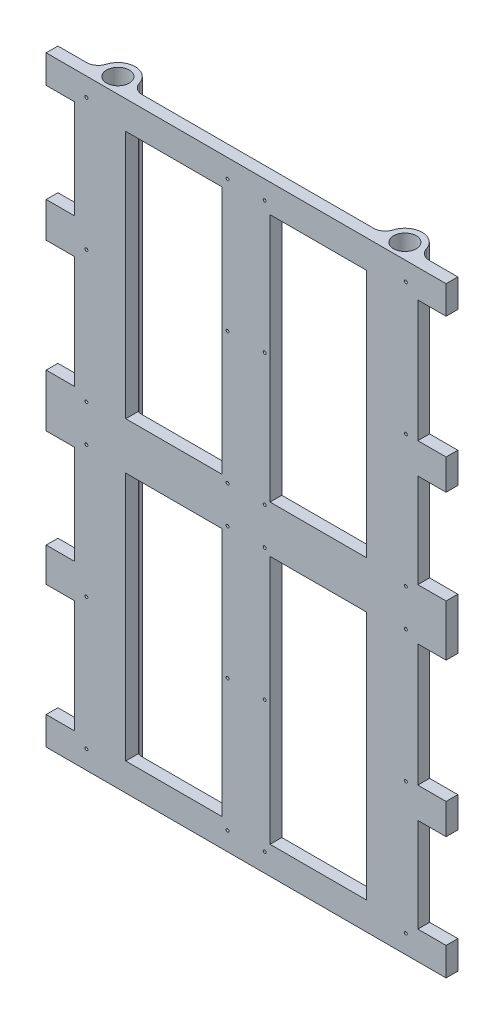
SolidWorks part; units mm, degrees
material "E-Glass Fiber"
ref_plane "Front Plane" through (0, 0, 0) normal (0, 0, 1) x (1, 0, 0)
ref_plane "Top Plane" through (0, 0, 0) normal (0, 1, 0) x (1, 0, 0)
ref_plane "Right Plane" through (0, 0, 0) normal (1, 0, 0) x (0, 0, -1)
other "Center of Mass"
sketch "Sketch1" plane through (0, 0, 0) normal (0, 1, 0) x (1, 0, 0)
  line L19 (85, -5) -> (85, 0)
  line L20 (85, -5) -> (-85, -5)
  line L24 (85, 0) -> (72.8176, 0)
  line L25 (-85, -5) -> (-85, 0)
  line L26 (85, -5) -> (-85, 0) construction
  line L27 (85, 0) -> (-85, -5) construction
  line L28 (0, 0) -> (0, -5) construction
  line L29 (-72.8176, 0) -> (-85, 0)
  line L30 (49.1824, 0) -> (-49.1824, 0)
  circle A29 centre (-61, 1.5) radius 4.825
  arc A30 (-68.1698, 0) -> (-53.8302, 0) centre (-61, 1.5) ccw construction
  arc A31 (-72.8176, 0) -> (-68.0234, 3.5801) centre (-72.8176, 5) ccw
  arc A32 (-53.9766, 3.5801) -> (-49.1824, 0) centre (-49.1824, 5) ccw
  arc A33 (-53.9766, 3.5801) -> (-68.0234, 3.5801) centre (-61, 1.5) ccw
  arc A34 (68.1698, 0) -> (53.8302, 0) centre (61, 1.5) cw construction
  arc A35 (53.9766, 3.5801) -> (68.0234, 3.5801) centre (61, 1.5) cw
  arc A36 (53.9766, 3.5801) -> (49.1824, 0) centre (49.1824, 5) cw
  arc A37 (72.8176, 0) -> (68.0234, 3.5801) centre (72.8176, 5) cw
  circle A38 centre (61, 1.5) radius 4.825
  point P1 (0, -2.5)
  dimension "D3" = 9.65
  dimension "D4" = 6.5
  dimension "D5" = 61
  dimension "D6" = 14.65
  dimension "D1" = 5
  dimension "D2" = 170
extrude "Boss-Extrude1" add sketch "Sketch1" along normal blind 255.6
sketch "Sketch2" plane through (0, 0, 0) normal (0, 0, -1) x (-1, 0, 0)
  line L0 (-85, 127.8) -> (85, 127.8) construction
  line L1 (-51.175, 11.8) -> (-10.175, 11.8)
  line L2 (-51.175, 11.8) -> (-51.175, 117.8)
  line L3 (-51.175, 243.6) -> (-10.175, 243.6)
  line L4 (-10.175, 11.8) -> (-10.175, 117.8)
  line L5 (-51.175, 11.8) -> (-10.175, 243.6) construction
  line L6 (-51.175, 243.6) -> (-10.175, 11.8) construction
  line L7 (-49.1824, 255.6) -> (49.1824, 255.6) construction
  line L8 (-10.175, 137.8) -> (-10.175, 243.6)
  line L9 (0, 255.6) -> (0, 0) construction
  line L10 (-93, 178.8) -> (-73, 178.8)
  line L11 (51.175, 11.8) -> (10.175, 11.8)
  line L12 (51.175, 11.8) -> (51.175, 117.8)
  line L13 (51.175, 243.6) -> (10.175, 243.6)
  line L14 (10.175, 11.8) -> (10.175, 117.8)
  line L15 (51.175, 11.8) -> (10.175, 243.6) construction
  line L16 (51.175, 243.6) -> (10.175, 11.8) construction
  line L17 (-56.175, 0) -> (-56.175, 255.6) construction
  line L18 (56.175, 255.6) -> (56.175, 0) construction
  line L19 (10.175, 137.8) -> (10.175, 243.6)
  line L20 (-51.175, 117.8) -> (-10.175, 117.8)
  line L22 (-51.175, 137.8) -> (-10.175, 137.8)
  line L24 (10.175, 137.8) -> (51.175, 137.8)
  line L25 (10.175, 117.8) -> (51.175, 117.8)
  line L26 (-51.175, 137.8) -> (-51.175, 243.6)
  line L27 (51.175, 137.8) -> (51.175, 243.6)
  line L28 (-93, 178.8) -> (-93, 138.8)
  line L29 (-93, 138.8) -> (-73, 138.8)
  line L30 (-73, 178.8) -> (-73, 138.8)
  line L31 (-93, 178.8) -> (-73, 138.8) construction
  line L32 (-93, 138.8) -> (-73, 178.8) construction
  line L33 (-85, 255.6) -> (-85, 0) construction
  line L34 (85, 255.6) -> (85, 0) construction
  line L35 (-93, 52) -> (-73, 52)
  line L36 (-73, 191.8) -> (-93, 191.8)
  line L37 (-73, 191.8) -> (-73, 243.6)
  line L38 (-73, 243.6) -> (-93, 243.6)
  line L39 (-93, 191.8) -> (-93, 243.6)
  line L40 (-73, 191.8) -> (-93, 243.6) construction
  line L41 (-73, 243.6) -> (-93, 191.8) construction
  line L42 (-93, 52) -> (-93, 12)
  line L43 (-93, 12) -> (-73, 12)
  line L44 (-73, 52) -> (-73, 12)
  line L53 (-93, 52) -> (-73, 12) construction
  line L54 (-93, 12) -> (-73, 52) construction
  line L55 (-73, 65) -> (-93, 65)
  line L56 (-73, 65) -> (-73, 117)
  line L57 (-73, 117) -> (-93, 117)
  line L58 (-93, 65) -> (-93, 117)
  line L59 (-73, 65) -> (-93, 117) construction
  line L60 (-73, 117) -> (-93, 65) construction
  line L61 (72.8176, 255.6) -> (85, 255.6) construction
  line L62 (-85, 0) -> (-72.8176, 0) construction
  line L67 (93, 201.6) -> (73, 201.6)
  line L68 (93, 201.6) -> (93, 243.6)
  line L73 (93, 243.6) -> (73, 243.6)
  line L74 (73, 201.6) -> (73, 243.6)
  line L75 (-85, 255.6) -> (-72.8176, 255.6) construction
  line L76 (93, 74.4) -> (73, 74.4)
  line L77 (93, 201.6) -> (73, 243.6) construction
  line L78 (93, 243.6) -> (73, 201.6) construction
  line L83 (73, 138.8) -> (93, 138.8)
  line L84 (73, 138.8) -> (73, 186.6)
  line L85 (73, 186.6) -> (93, 186.6)
  line L86 (93, 138.8) -> (93, 186.6)
  line L87 (73, 138.8) -> (93, 186.6) construction
  line L88 (73, 186.6) -> (93, 138.8) construction
  line L89 (93, 74.4) -> (93, 116.4)
  line L90 (93, 116.4) -> (73, 116.4)
  line L91 (73, 74.4) -> (73, 116.4)
  line L92 (93, 74.4) -> (73, 116.4) construction
  line L93 (93, 116.4) -> (73, 74.4) construction
  line L94 (73, 12) -> (93, 12)
  line L95 (73, 12) -> (73, 59.9)
  line L96 (73, 59.9) -> (93, 59.9)
  line L97 (93, 12) -> (93, 59.9)
  line L98 (73, 12) -> (93, 59.9) construction
  line L99 (73, 59.9) -> (93, 12) construction
  line L100 (72.8176, 0) -> (85, 0) construction
  point P0 (-30.675, 127.7)
  point P5 (-83, 158.8)
  point P14 (30.675, 127.7)
  point P23 (0, 127.8)
  point P39 (-83, 217.7)
  point P44 (-83, 32)
  point P49 (-83, 91)
  point P54 (83, 222.6)
  point P61 (83, 162.7)
  point P70 (83, 95.4)
  point P75 (83, 35.95)
  dimension "D1" = 12
  dimension "D2" = 5
  dimension "D3" = 41
  dimension "D4" = 12
  dimension "D5" = 5
  dimension "D6" = 41
  dimension "D7" = 20
  dimension "D8" = 11
  dimension "D9" = 40
  dimension "D10" = 73
  dimension "D11" = 20
  dimension "D12" = 13
  dimension "D13" = 12
  dimension "D14" = 40
  dimension "D15" = 20
  dimension "D16" = 13
  dimension "D17" = 52
  dimension "D18" = 73
  dimension "D19" = 20
  dimension "D20" = 12
  dimension "D21" = 12
  dimension "D22" = 15
  dimension "D23" = 42
  dimension "D24" = 73
  dimension "D25" = 11
  dimension "D26" = 20
  dimension "D27" = 14.5
  dimension "D28" = 42
  dimension "D29" = 73
  dimension "D30" = 12
extrude "Cut-Extrude2" cut sketch "Sketch2" against normal through all and the other way through all
sketch "Sketch3" plane through (0, 0, 5) normal (0, 0, -1) x (-1, 0, 0)
  line L0 (0, 0) -> (0, 255.6) construction
  line L1 (-49.1824, 0) -> (49.1824, 0) construction
  line L5 (255.8, 127.8) -> (0, 127.8) construction
  point P0 (-67.9, 7.9)
  point P1 (-7.9, 7.9)
  point P3 (-7.9, 63.9)
  point P5 (-67.9, 63.9)
  point P7 (-67.9, 119.9)
  point P9 (-7.9, 119.9)
  point P23 (7.9, 119.9)
  point P24 (67.9, 119.9)
  point P25 (67.9, 63.9)
  point P26 (7.9, 63.9)
  point P27 (7.9, 7.9)
  point P28 (67.9, 7.9)
  point P31 (67.9, 247.7)
  point P32 (7.9, 247.7)
  point P33 (7.9, 191.7)
  point P34 (67.9, 191.7)
  point P35 (67.9, 135.7)
  point P36 (7.9, 135.7)
  point P37 (-7.9, 135.7)
  point P38 (-67.9, 135.7)
  point P39 (-67.9, 191.7)
  point P40 (-7.9, 191.7)
  point P41 (-7.9, 247.7)
  point P42 (-67.9, 247.7)
hole_wizard "Ø1.25 (1.25) Diameter Hole1" positions "Sketch3" profile "Sketch4" hole size "Ø1.25" standard "ANSI Metric" end condition through all
sketch "Sketch4" plane through (67.9, 7.9, 5) normal (1, 0, 0) x (0, -1, 0)
  line L0 (0, 0) -> (0, 13.825)
  line L1 (0, 13.825) -> (0.625, 13.825)
  line L2 (0.625, 13.825) -> (0.625, 0)
  line L5 (0.625, 0) -> (0, 0)
  line L11 (0, -6.35) -> (0, 107.95) construction
  dimension "Thru Hole Dia." = 1.25
  dimension "Thru Hole Depth" = 13.825
sketch "Sketch5" plane through (0, 0, 0) normal (0, 0, -1) x (-1, 0, 0)
  line L0 (255.8, 127.8) -> (0, 127.8) construction
  line L1 (0, 255.6) -> (0, 127.8) construction
  circle A24 centre (-67.9, 247.7) radius 1.5
  circle A25 centre (-7.9, 247.7) radius 1.5
  circle A26 centre (-67.9, 191.7) radius 1.5
  circle A27 centre (-67.9, 135.7) radius 1.5
  circle A28 centre (-7.9, 135.7) radius 1.5
  circle A29 centre (-7.9, 191.7) radius 1.5
  circle A30 centre (-7.9, 63.9) radius 1.5
  circle A31 centre (-7.9, 119.9) radius 1.5
  circle A32 centre (-67.9, 119.9) radius 1.5
  circle A33 centre (-67.9, 63.9) radius 1.5
  circle A34 centre (-7.9, 7.9) radius 1.5
  circle A35 centre (-67.9, 7.9) radius 1.5
  circle A36 centre (67.9, 7.9) radius 1.5
  circle A37 centre (7.9, 7.9) radius 1.5
  circle A38 centre (67.9, 63.9) radius 1.5
  circle A39 centre (67.9, 119.9) radius 1.5
  circle A40 centre (7.9, 119.9) radius 1.5
  circle A41 centre (7.9, 63.9) radius 1.5
  circle A42 centre (7.9, 191.7) radius 1.5
  circle A43 centre (7.9, 135.7) radius 1.5
  circle A44 centre (67.9, 135.7) radius 1.5
  circle A45 centre (67.9, 191.7) radius 1.5
  circle A46 centre (7.9, 247.7) radius 1.5
  circle A47 centre (67.9, 247.7) radius 1.5
  dimension "D1" = 3
extrude "Cut-Extrude3" cut sketch "Sketch5" along normal through all
equation "\"rod_d\"= 9.65"
equation "\"big_bearing_id\"= 140mm"
equation "\"rod_offset_c2c\"= \"big_bearing_id\" / 2 - \"rod_d\" / 2 - 1.5"
